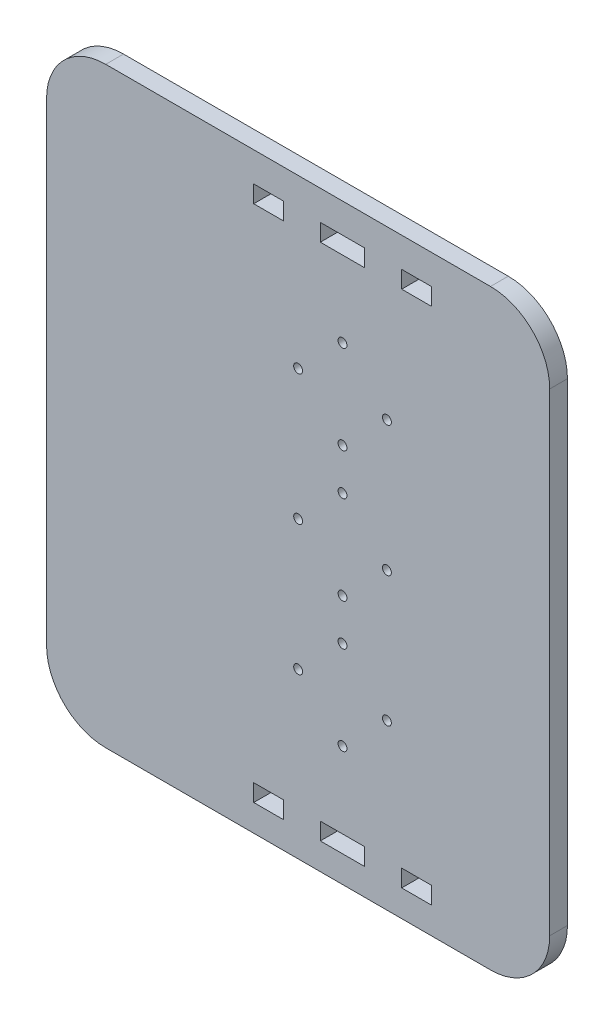
SolidWorks part; units mm, degrees
ref_plane "Alzado" through (0, 0, 0) normal (0, 0, 1) x (1, 0, 0)
ref_plane "Planta" through (0, 0, 0) normal (0, 1, 0) x (1, 0, 0)
ref_plane "Vista lateral" through (0, 0, 0) normal (1, 0, 0) x (0, 0, -1)
sketch "Sketch1" plane through (0, 0, 0) normal (0, 0, 1) x (1, 0, 0)
  line L0 (-15, 42.35) -> (-10, 42.35)
  line L1 (-10, 45.25) -> (-3.75, 45.25)
  line L2 (-15, 42.35) -> (-15, -42.35)
  line L3 (10, -42.35) -> (15, -42.35)
  line L4 (15, 42.35) -> (15, -42.35)
  line L5 (-15, 45.25) -> (15, -45.25) construction
  line L6 (-15, -45.25) -> (15, 45.25) construction
  line L7 (-10, 42.35) -> (-10, 45.25)
  line L8 (-3.75, 45.25) -> (-3.75, 42.35)
  line L9 (-3.75, 42.35) -> (3.75, 42.35)
  line L10 (3.75, 42.35) -> (3.75, 45.25)
  line L11 (10, 45.25) -> (10, 42.35)
  line L12 (10, 42.35) -> (15, 42.35)
  line L13 (0, 0) -> (0, 42.35) construction
  line L14 (3.75, 45.25) -> (10, 45.25)
  line L15 (-15, 42.35) -> (-15, 45.25)
  line L16 (-15, 45.25) -> (-10, 45.25)
  line L17 (10, 45.25) -> (15, 45.25)
  line L18 (15, 45.25) -> (15, 42.35)
  line L19 (0, 0) -> (15, 0) construction
  line L20 (10, -45.25) -> (10, -42.35)
  line L21 (3.75, -45.25) -> (10, -45.25)
  line L22 (3.75, -42.35) -> (3.75, -45.25)
  line L23 (-3.75, -42.35) -> (3.75, -42.35)
  line L24 (-3.75, -45.25) -> (-3.75, -42.35)
  line L25 (-10, -45.25) -> (-3.75, -45.25)
  line L26 (-10, -42.35) -> (-10, -45.25)
  line L27 (-15, -42.35) -> (-10, -42.35)
  line L28 (-15, -42.35) -> (-15, -45.25)
  line L29 (-15, -45.25) -> (-10, -45.25)
  line L30 (10, -45.25) -> (15, -45.25)
  line L31 (15, -45.25) -> (15, -42.35)
  line L32 (15, 22) -> (-15, 22) construction
  line L33 (-15, -22) -> (15, -22) construction
  line L34 (-50, 40.25) -> (-50, -39.75)
  line L35 (-40, -49.75) -> (25, -49.75)
  line L36 (35, -39.75) -> (35, 40.25)
  line L37 (25, 50.25) -> (-40, 50.25)
  line L38 (-10, 42.35) -> (-3.75, 42.35)
  line L39 (3.75, 42.35) -> (10, 42.35)
  line L40 (-10, -42.35) -> (-3.75, -42.35)
  line L41 (3.75, -42.35) -> (10, -42.35)
  line L42 (-3.75, 45.25) -> (3.75, 45.25)
  line L43 (-3.75, -45.25) -> (3.75, -45.25)
  circle A0 centre (0, 22) radius 7.5 construction
  circle A1 centre (0, 0) radius 7.5 construction
  circle A2 centre (0, -22) radius 7.5 construction
  circle A3 centre (0, 29.5) radius 0.75
  circle A4 centre (7.5, 22) radius 0.75
  circle A5 centre (0, 14.5) radius 0.75
  circle A6 centre (-7.5, 22) radius 0.75
  circle A7 centre (0, 7.5) radius 0.75
  circle A8 centre (-7.5, 0) radius 0.75
  circle A9 centre (0, -7.5) radius 0.75
  circle A10 centre (7.5, 0) radius 0.75
  circle A11 centre (0, -14.5) radius 0.75
  circle A12 centre (-7.5, -22) radius 0.75
  circle A13 centre (0, -29.5) radius 0.75
  circle A14 centre (7.5, -22) radius 0.75
  arc A15 (-50, -39.75) -> (-40, -49.75) centre (-40, -39.75) ccw
  arc A16 (25, -49.75) -> (35, -39.75) centre (25, -39.75) ccw
  arc A17 (35, 40.25) -> (25, 50.25) centre (25, 40.25) ccw
  arc A18 (-50, 40.25) -> (-40, 50.25) centre (-40, 40.25) cw
  point P0 (0, 0)
  point P72 (35, 50.25)
  point P75 (-50, 50.25)
  dimension "D9" = 15
  dimension "D10" = 1.5
  dimension "D15" = 10
  dimension "D1" = 90.5
  dimension "D2" = 30
  dimension "D3" = 7.5
  dimension "D4" = 5
  dimension "D5" = 5
  dimension "D6" = 2.9
  dimension "D7" = 22
  dimension "D8" = 22
  dimension "D11" = 20
  dimension "D12" = 85
  dimension "D13" = 5
  dimension "D14" = 100
extrude "Boss-Extrude1" add sketch "Sketch1" along normal blind 3 contours A18 L34 A15 L35 A16 L36 A17 L37 L43 L25 L29 L28 L2 L15 L16 L1 L42 L14 L17 L18 L4 L31 L30 L21 | L23 L41 L3 L4 L12 L39 L9 L38 L0 L2 L27 L40 A14 A13 A12 A11 A10 A9 A8 A7 A6 A5 A4 A3 | L7 L38 L8 L1 | L10 L39 L11 L14 | L40 L26 L25 L24 | L41 L22 L21 L20
